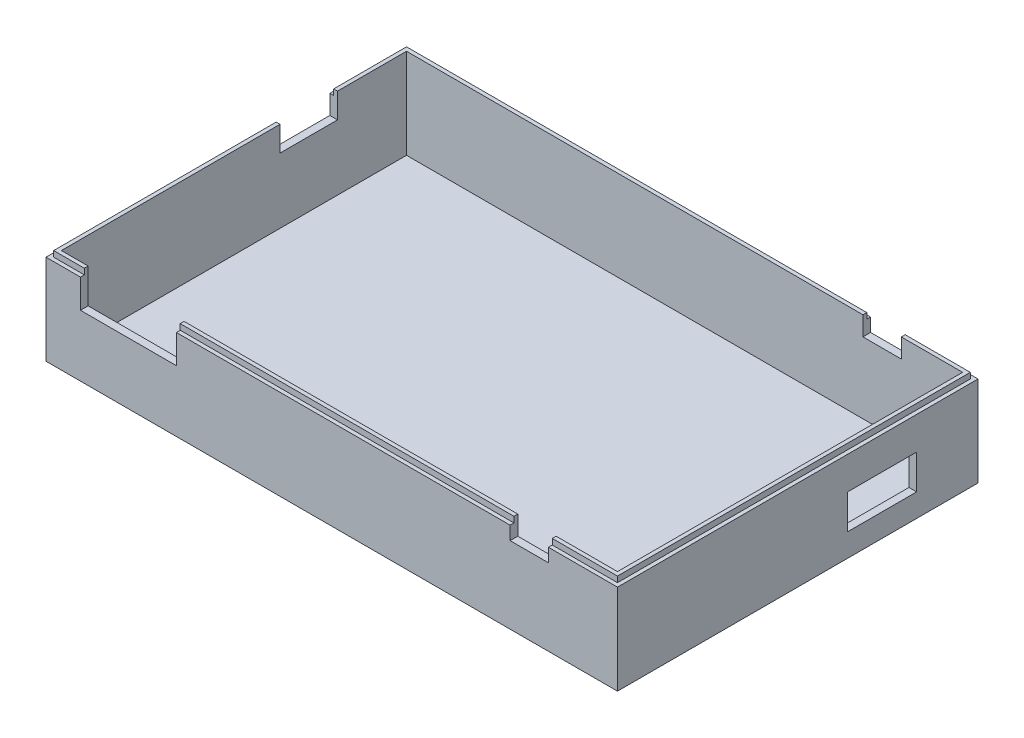
SolidWorks part; units mm, degrees
ref_plane "Front Plane" through (0, 0, 0) normal (0, 0, 1) x (1, 0, 0)
ref_plane "Top Plane" through (0, 0, 0) normal (0, 1, 0) x (1, 0, 0)
ref_plane "Right Plane" through (0, 0, 0) normal (1, 0, 0) x (0, 0, -1)
sketch "Sketch2" plane through (0, 0, 0) normal (0, 1, 0) x (1, 0, 0)
  line L1 (-72.5, -45) -> (72.5, -45)
  line L2 (-72.5, -45) -> (-72.5, 45)
  line L3 (-72.5, 45) -> (72.5, 45)
  line L4 (72.5, -45) -> (72.5, 45)
  line L5 (-72.5, -45) -> (72.5, 45) construction
  line L6 (-72.5, 45) -> (72.5, -45) construction
  point P0 (0, 0)
  dimension "D1" = 145
  dimension "D2" = 90
extrude "Boss-Extrude1" add sketch "Sketch2" along normal blind 1.5
sketch "Sketch3" plane through (0, 0, 0) normal (0, 1, 0) x (1, 0, 0)
  line L14 (-74.5, -47) -> (74.5, -47)
  line L15 (74.5, -47) -> (74.5, 47)
  line L16 (74.5, 47) -> (-74.5, 47)
  line L17 (-74.5, 47) -> (-74.5, -47)
  line L18 (-74.5, -47) -> (74.5, -47)
  line L19 (74.5, -47) -> (74.5, 47)
  line L20 (74.5, 47) -> (-74.5, 47)
  line L21 (-74.5, 47) -> (-74.5, -47)
  line L32 (72.5, -45) -> (72.5, 45)
  line L33 (-72.5, -45) -> (72.5, -45)
  line L34 (-72.5, 45) -> (-72.5, -45)
  line L35 (72.5, 45) -> (-72.5, 45)
  line L36 (72.5, -45) -> (72.5, 45)
  line L37 (-72.5, -45) -> (72.5, -45)
  line L38 (-72.5, 45) -> (-72.5, -45)
  line L39 (72.5, 45) -> (-72.5, 45)
  dimension "D1" = 2
  dimension "D2" = 0
extrude "Boss-Extrude2" add sketch "Sketch3" along normal blind 25
sketch "Sketch4" plane through (0, 0, 47) normal (0, 0, 1) x (1, 0, 0)
  line L0 (-74.5, 0) -> (74.5, 0) construction
  line L1 (-65.5, 31) -> (-40.5, 31)
  line L2 (-65.5, 31) -> (-65.5, 16)
  line L3 (-65.5, 16) -> (-40.5, 16)
  line L4 (-40.5, 31) -> (-40.5, 16)
  line L5 (-65.5, 31) -> (-40.5, 16) construction
  line L6 (-65.5, 16) -> (-40.5, 31) construction
  line L7 (-74.5, 25) -> (-74.5, 0) construction
  point P0 (-53, 23.5)
  dimension "D1" = 25
  dimension "D2" = 15
  dimension "D3" = 16
  dimension "D4" = 9
extrude "Cut-Extrude1" cut sketch "Sketch4" against normal up to next
sketch "Sketch5" plane through (74.5, 0, 0) normal (1, 0, 0) x (0, 0, -1)
  line L0 (47, 25) -> (47, 0) construction
  line L1 (13, 15) -> (31, 15)
  line L2 (13, 15) -> (13, 6)
  line L3 (13, 6) -> (31, 6)
  line L4 (31, 15) -> (31, 6)
  line L5 (13, 15) -> (31, 6) construction
  line L6 (13, 6) -> (31, 15) construction
  line L7 (-47, 0) -> (47, 0) construction
  point P0 (22, 10.5)
  dimension "D1" = 18
  dimension "D2" = 9
  dimension "D3" = 16
  dimension "D4" = 6
extrude "Cut-Extrude2" cut sketch "Sketch5" against normal up to next
sketch "Sketch6" plane through (0, 0, 47) normal (0, 0, 1) x (1, 0, 0)
  line L0 (-40.5, 25) -> (74.5, 25) construction
  line L1 (46.5, 20) -> (56.5, 20)
  line L2 (46.5, 20) -> (46.5, 25)
  line L3 (46.5, 25) -> (56.5, 25)
  line L4 (56.5, 20) -> (56.5, 25)
  line L5 (46.5, 20) -> (56.5, 25) construction
  line L6 (46.5, 25) -> (56.5, 20) construction
  line L7 (74.5, 25) -> (74.5, 0) construction
  point P0 (51.5, 22.5)
  dimension "605" = 5
  dimension "D2" = 10
  dimension "D3" = 0
  dimension "D4" = 18
extrude "Cut-Extrude3" cut sketch "Sketch6" against normal through all
sketch "Sketch7" plane through (-74.5, 0, 0) normal (-1, 0, 0) x (0, 0, 1)
  line L0 (-47, 25) -> (47, 25) construction
  line L1 (-27, 25) -> (-12, 25)
  line L2 (-27, 25) -> (-27, 18.5)
  line L3 (-27, 18.5) -> (-12, 18.5)
  line L4 (-12, 25) -> (-12, 18.5)
  line L5 (-27, 25) -> (-12, 18.5) construction
  line L6 (-27, 18.5) -> (-12, 25) construction
  line L7 (-47, 25) -> (-47, 0) construction
  point P0 (-19.5, 21.75)
  dimension "D1" = 6.5
  dimension "D2" = 15
  dimension "D3" = 0
  dimension "D4" = 20
extrude "Cut-Extrude4" cut sketch "Sketch7" against normal up to next
sketch "Sketch9" plane through (0, 25, 0) normal (0, 1, 0) x (1, 0, 0)
  line L24 (-72.5, 12) -> (-74.5, 12)
  line L25 (-74.5, 12) -> (-74.5, -47)
  line L26 (-74.5, -47) -> (-65.5, -47)
  line L27 (-65.5, -47) -> (-65.5, -45)
  line L28 (-65.5, -45) -> (-72.5, -45)
  line L29 (-72.5, -45) -> (-72.5, 12)
  line L30 (-73.5, 12) -> (-74.5, 12)
  line L31 (-74.5, 12) -> (-74.5, -47)
  line L32 (-74.5, -47) -> (-65.5, -47)
  line L33 (-65.5, -47) -> (-65.5, -46)
  line L42 (-74.5, 27) -> (-72.5, 27)
  line L43 (-72.5, 27) -> (-72.5, 45)
  line L44 (-72.5, 45) -> (46.5, 45)
  line L45 (46.5, 45) -> (46.5, 47)
  line L46 (46.5, 47) -> (-74.5, 47)
  line L47 (-74.5, 47) -> (-74.5, 27)
  line L48 (-74.5, 27) -> (-73.5, 27)
  line L51 (46.5, 46) -> (46.5, 47)
  line L52 (46.5, 47) -> (-74.5, 47)
  line L53 (-74.5, 47) -> (-74.5, 27)
  line L60 (46.5, 46) -> (-73.5, 46)
  line L61 (-73.5, 46) -> (-73.5, 27)
  line L62 (-73.5, 12) -> (-73.5, -46)
  line L63 (-73.5, -46) -> (-65.5, -46)
  line L64 (56.5, -45) -> (56.5, -47)
  line L65 (56.5, -47) -> (74.5, -47)
  line L66 (74.5, -47) -> (74.5, 47)
  line L67 (74.5, 47) -> (56.5, 47)
  line L68 (56.5, 47) -> (56.5, 45)
  line L69 (56.5, 45) -> (72.5, 45)
  line L70 (72.5, 45) -> (72.5, -45)
  line L71 (72.5, -45) -> (56.5, -45)
  line L72 (56.5, -46) -> (56.5, -47)
  line L73 (56.5, -47) -> (74.5, -47)
  line L74 (74.5, -47) -> (74.5, 47)
  line L75 (74.5, 47) -> (56.5, 47)
  line L76 (56.5, 47) -> (56.5, 46)
  line L80 (46.5, -47) -> (46.5, -45)
  line L81 (46.5, -45) -> (-40.5, -45)
  line L82 (-40.5, -45) -> (-40.5, -47)
  line L83 (-40.5, -47) -> (46.5, -47)
  line L84 (46.5, -47) -> (46.5, -46)
  line L86 (-40.5, -46) -> (-40.5, -47)
  line L87 (-40.5, -47) -> (46.5, -47)
  line L88 (-40.5, -46) -> (46.5, -46)
  line L89 (56.5, -46) -> (73.5, -46)
  line L90 (73.5, -46) -> (73.5, 46)
  line L91 (73.5, 46) -> (56.5, 46)
  dimension "D1" = 0
  dimension "D2" = 0
  dimension "D3" = 0
  dimension "D4" = 0
  dimension "D5" = 1
extrude "Cut-Extrude5" cut sketch "Sketch9" against normal blind 1.5
